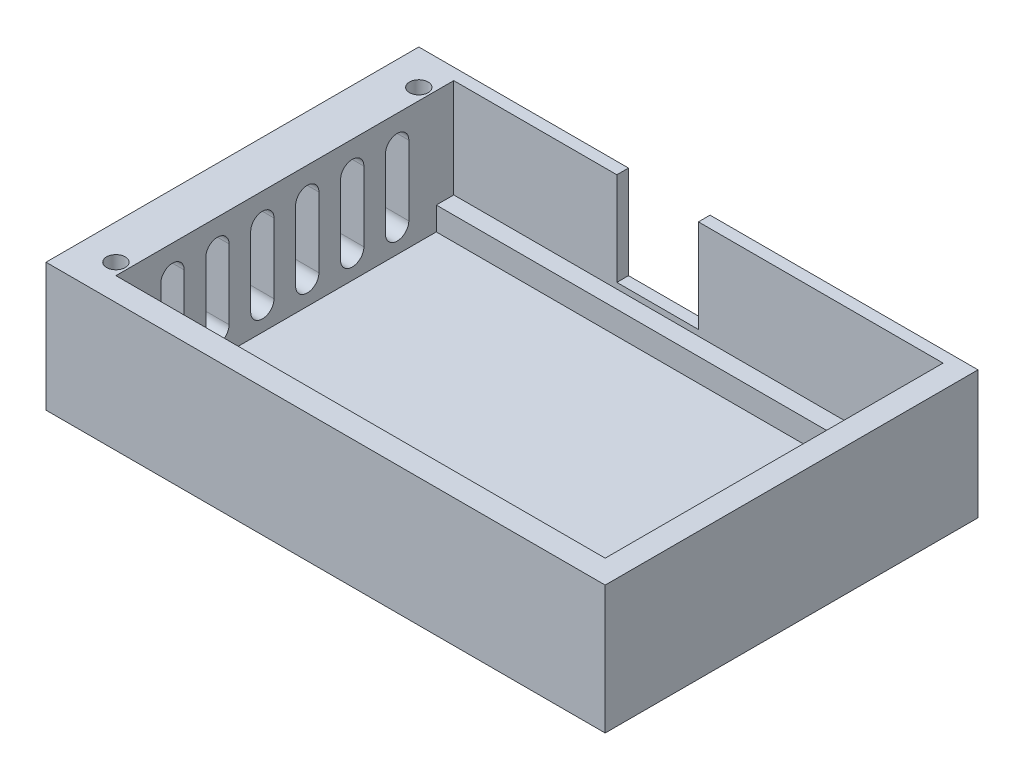
SolidWorks part; units mm, degrees
ref_plane "Front Plane" through (0, 0, 0) normal (0, 0, 1) x (1, 0, 0)
ref_plane "Top Plane" through (0, 0, 0) normal (0, 1, 0) x (1, 0, 0)
ref_plane "Right Plane" through (0, 0, 0) normal (1, 0, 0) x (0, 0, -1)
sketch "Sketch1" plane through (0, 0, 0) normal (0, 1, 0) x (1, 0, 0)
  line L1 (-48, 32) -> (48, 32)
  line L2 (-48, 32) -> (-48, -32)
  line L3 (-48, -32) -> (48, -32)
  line L4 (48, 32) -> (48, -32)
  line L5 (-48, 32) -> (48, -32) construction
  line L6 (-48, -32) -> (48, 32) construction
  point P0 (0, 0)
  dimension "D1" = 96
  dimension "D2" = 64
extrude "Boss-Extrude1" add sketch "Sketch1" along normal blind 1
sketch "Sketch2" plane through (0, 1, 0) normal (0, 1, 0) x (1, 0, 0)
  line L1 (-40, 30) -> (32, 30)
  line L2 (-40, 30) -> (-40, -22)
  line L3 (-40, -22) -> (32, -22)
  line L4 (32, 30) -> (32, -22)
  line L5 (-40, 30) -> (32, -22) construction
  line L6 (-40, -22) -> (32, 30) construction
  line L7 (48, 32) -> (-48, 32)
  line L8 (48, 32) -> (48, -32)
  line L9 (48, -32) -> (-48, -32)
  line L10 (-48, 32) -> (-48, -32)
  line L11 (48, 32) -> (-48, -32) construction
  line L12 (48, -32) -> (-48, 32) construction
  point P0 (0, 0)
  point P6 (0, 0)
  dimension "D1" = 72
  dimension "D2" = 52
  dimension "D3" = 2
  dimension "D4" = 8
extrude "Boss-Extrude2" add sketch "Sketch2" along normal blind 21
sketch "Sketch3" plane through (0, 1, 0) normal (0, 1, 0) x (1, 0, 0)
  line L0 (32, -22) -> (32, 30) construction
  line L1 (-40, -22) -> (32, -22)
  line L2 (-40, -22) -> (-40, -19)
  line L3 (-40, -19) -> (32, -19)
  line L4 (32, -22) -> (32, -19)
  line L5 (0, 4) -> (32, 4) construction
  line L6 (-40, 27) -> (32, 27)
  line L7 (32, 30) -> (32, 27)
  line L8 (-40, 30) -> (32, 30)
  line L9 (-40, 30) -> (-40, 27)
  point P15 (32, 4)
  dimension "D1" = 3
extrude "Boss-Extrude3" add sketch "Sketch3" along normal blind 4
sketch "Sketch4" plane through (0, 22, 0) normal (0, 1, 0) x (1, 0, 0)
  line L0 (32, -22) -> (32, 30) construction
  line L1 (-40, -22) -> (32, -22)
  line L2 (-40, -22) -> (-40, -28)
  line L3 (-40, -28) -> (32, -28)
  line L4 (32, -22) -> (32, -28)
  line L5 (-48, -32) -> (48, -32) construction
  line L6 (32, 30) -> (44, 30)
  line L7 (32, 30) -> (32, -28)
  line L8 (32, -28) -> (44, -28)
  line L9 (44, 30) -> (44, -28)
  line L10 (48, -32) -> (48, 32) construction
  line M13 (32, 30) -> (32, -22)
  line M14 (32, -22) -> (-40, -22)
  dimension "D1" = 4
  dimension "D2" = 4
extrude "Cut-Extrude1" cut sketch "Sketch4" against normal blind 14 contours L9 L6 L4 L8 M13 | L4 L2 L3 M14
sketch "Sketch5" plane through (0, 8, 0) normal (0, 1, 0) x (1, 0, 0)
  line L1 (44, -28) -> (38, -28)
  line L2 (44, -28) -> (44, -12)
  line L3 (44, -12) -> (38, -12)
  line L4 (38, -28) -> (38, -12)
  dimension "D1" = 6
  dimension "D2" = 16
extrude "Cut-Extrude2" cut sketch "Sketch5" against normal through all
sketch "Sketch6" plane through (0, 0, -32) normal (0, 0, -1) x (-1, 0, 0)
  line L0 (-48, 22) -> (48, 22) construction
  line L1 (-2, 22) -> (12, 22)
  line L2 (-2, 22) -> (-2, 6)
  line L3 (-2, 6) -> (12, 6)
  line L4 (12, 22) -> (12, 6)
  line L5 (-48, 22) -> (-48, 0) construction
  line L6 (48, 22) -> (48, 0) construction
  line L7 (-48, 0) -> (48, 0) construction
  dimension "D1" = 46
  dimension "D2" = 36
  dimension "D3" = 6
extrude "Cut-Extrude3" cut sketch "Sketch6" against normal up to next and the other way through all
sketch "Sketch7" plane through (0, 22, 0) normal (0, 1, 0) x (1, 0, 0)
  line L0 (0, 0) -> (0, 9.2505) construction
  line L1 (0, 0) -> (14.4322, 0) construction
  line L2 (-48, 32) -> (-48, -32) construction
  line L3 (-12, 32) -> (-48, 32) construction
  circle A0 centre (-42, 26) radius 1.6
  circle A1 centre (-42, -26) radius 1.6
  circle A2 centre (42, 26) radius 1.6
  circle A3 centre (42, -4) radius 1.6
  dimension "D1" = 3.2
  dimension "D2" = 6
  dimension "D3" = 6
  dimension "D4" = 30
extrude "Cut-Extrude4" cut sketch "Sketch7" against normal through all
sketch "Sketch9" plane through (-48, 0, 0) normal (-1, 0, 0) x (0, 0, 1)
  line L0 (-32, 11) -> (32, 11) construction
  line L1 (-32, 22) -> (-32, 0) construction
  line L2 (32, 22) -> (32, 0) construction
  line L6 (-20.2857, 17) -> (-20.2857, 5) construction
  line L7 (-18.2857, 17) -> (-18.2857, 5)
  line L8 (-22.2857, 17) -> (-22.2857, 5)
  line L9 (-12.5714, 17) -> (-12.5714, 5) construction
  line L10 (-10.5714, 17) -> (-10.5714, 5)
  line L11 (-14.5714, 17) -> (-14.5714, 5)
  line L12 (-4.8571, 17) -> (-4.8571, 5) construction
  line L13 (-2.8571, 17) -> (-2.8571, 5)
  line L14 (-6.8571, 17) -> (-6.8571, 5)
  line L15 (2.8571, 17) -> (2.8571, 5) construction
  line L16 (4.8571, 17) -> (4.8571, 5)
  line L17 (0.8571, 17) -> (0.8571, 5)
  line L18 (10.5714, 17) -> (10.5714, 5) construction
  line L19 (12.5714, 17) -> (12.5714, 5)
  line L20 (8.5714, 17) -> (8.5714, 5)
  line L21 (18.2857, 17) -> (18.2857, 5) construction
  line L22 (20.2857, 17) -> (20.2857, 5)
  line L23 (16.2857, 17) -> (16.2857, 5)
  arc A2 (-18.2857, 17) -> (-22.2857, 17) centre (-20.2857, 17) ccw
  arc A3 (-22.2857, 5) -> (-18.2857, 5) centre (-20.2857, 5) ccw
  arc A4 (-10.5714, 17) -> (-14.5714, 17) centre (-12.5714, 17) ccw
  arc A5 (-14.5714, 5) -> (-10.5714, 5) centre (-12.5714, 5) ccw
  arc A6 (-2.8571, 17) -> (-6.8571, 17) centre (-4.8571, 17) ccw
  arc A7 (-6.8571, 5) -> (-2.8571, 5) centre (-4.8571, 5) ccw
  arc A8 (4.8571, 17) -> (0.8571, 17) centre (2.8571, 17) ccw
  arc A9 (0.8571, 5) -> (4.8571, 5) centre (2.8571, 5) ccw
  arc A10 (12.5714, 17) -> (8.5714, 17) centre (10.5714, 17) ccw
  arc A11 (8.5714, 5) -> (12.5714, 5) centre (10.5714, 5) ccw
  arc A12 (20.2857, 17) -> (16.2857, 17) centre (18.2857, 17) ccw
  arc A13 (16.2857, 5) -> (20.2857, 5) centre (18.2857, 5) ccw
  point P17 (-20.2857, 11)
  point P24 (-12.5714, 11)
  point P31 (-4.8571, 11)
  point P38 (2.8571, 11)
  point P45 (10.5714, 11)
  point P52 (18.2857, 11)
extrude "Cut-Extrude5" cut sketch "Sketch9" against normal up to surface (8 mm away) up to face at (-40, 8.2, 2.4)
